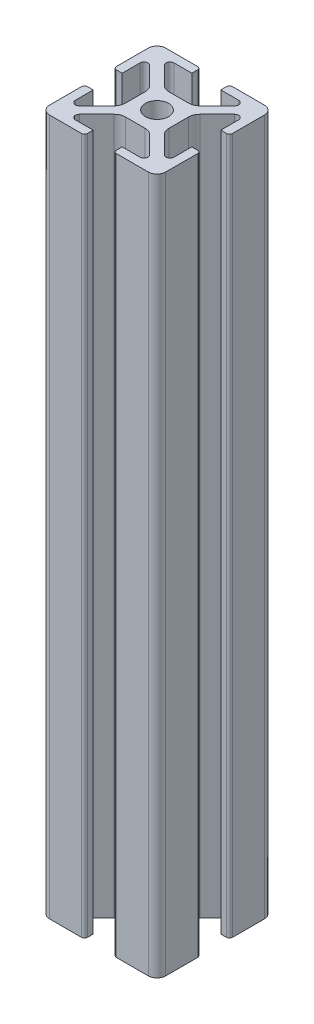
SolidWorks part; units mm, degrees
ref_plane "Plan de face" through (0, 0, 0) normal (0, 0, 1) x (1, 0, 0)
ref_plane "Plan de dessus" through (0, 0, 0) normal (0, 1, 0) x (1, 0, 0)
ref_plane "Plan de droite" through (0, 0, 0) normal (1, 0, 0) x (0, 0, -1)
sketch "Esquisse1" plane through (0, 0, 0) normal (0, 1, 0) x (1, 0, 0)
  line L0 (-5.6497, 11.1927) -> (14.3503, 11.1927) construction
  line L1 (14.3503, 11.1927) -> (14.3503, -8.8073) construction
  line L2 (14.3503, -8.8073) -> (-5.6497, -8.8073) construction
  line L3 (-5.6497, -8.8073) -> (-5.6497, 11.1927) construction
  line L4 (-5.6497, 11.1927) -> (14.3503, -8.8073) construction
  line L5 (-5.6497, -8.8073) -> (14.3503, 11.1927) construction
  line L6 (-5.6497, 9.6927) -> (-5.6497, 4.1927)
  line L7 (-5.1497, 3.6927) -> (-4.1497, 3.6927)
  line L8 (-4.1497, 3.6927) -> (-4.1497, 6.7528)
  line L9 (-2.9547, 7.2478) -> (0.0145, 4.2785)
  line L10 (0.6003, 2.8643) -> (0.6003, -0.4788)
  line L11 (0.0145, -1.8931) -> (-2.9547, -4.8623)
  line L12 (-4.1497, -4.3673) -> (-4.1497, -1.3073)
  line L13 (-4.1497, -1.3073) -> (-5.1497, -1.3073)
  line L14 (-5.6497, -1.8073) -> (-5.6497, -7.3073)
  line L15 (-4.1497, -8.8073) -> (1.3503, -8.8073)
  line L16 (1.8503, -8.3073) -> (1.8503, -7.3073)
  line L17 (1.8503, -7.3073) -> (-1.2098, -7.3073)
  line L18 (-1.7047, -6.1123) -> (1.2645, -3.1431)
  line L19 (2.6787, -2.5573) -> (6.0219, -2.5573)
  line L20 (7.4361, -3.1431) -> (10.4053, -6.1123)
  line L21 (9.9103, -7.3073) -> (6.8503, -7.3073)
  line L22 (6.8503, -7.3073) -> (6.8503, -8.3073)
  line L23 (7.3503, -8.8073) -> (12.8503, -8.8073)
  line L24 (14.3503, -7.3073) -> (14.3503, -1.8073)
  line L25 (13.8503, -1.3073) -> (12.8503, -1.3073)
  line L26 (12.8503, -1.3073) -> (12.8503, -4.3673)
  line L27 (11.6553, -4.8623) -> (8.6861, -1.8931)
  line L28 (8.1003, -0.4788) -> (8.1003, 2.8643)
  line L29 (8.6861, 4.2785) -> (11.6553, 7.2478)
  line L30 (12.8503, 6.7528) -> (12.8503, 3.6927)
  line L31 (12.8503, 3.6927) -> (13.8503, 3.6927)
  line L32 (14.3503, 4.1927) -> (14.3503, 9.6927)
  line L33 (12.8503, 11.1927) -> (7.3503, 11.1927)
  line L34 (6.8503, 10.6927) -> (6.8503, 9.6927)
  line L35 (6.8503, 9.6927) -> (9.9103, 9.6927)
  line L36 (10.4053, 8.4978) -> (7.4361, 5.5285)
  line L37 (6.0219, 4.9427) -> (2.6787, 4.9427)
  line L38 (1.2645, 5.5285) -> (-1.7047, 8.4978)
  line L39 (-1.2098, 9.6927) -> (1.8503, 9.6927)
  line L40 (1.8503, 9.6927) -> (1.8503, 10.6927)
  line L41 (1.3503, 11.1927) -> (-4.1497, 11.1927)
  line L42 (-4.1497, -6.0573) -> (-2.8997, -7.3073) construction
  line L43 (0.6003, -1.3073) -> (1.8503, -2.5573) construction
  line L44 (0.6003, 3.6927) -> (1.8503, 4.9427) construction
  line L45 (-4.1497, 8.4427) -> (-2.8997, 9.6927) construction
  line L46 (12.8503, 8.4427) -> (11.6003, 9.6927) construction
  line L47 (8.1003, 3.6927) -> (6.8503, 4.9427) construction
  line L48 (12.8503, -6.0573) -> (11.6003, -7.3073) construction
  line L49 (8.1003, -1.3073) -> (6.8503, -2.5573) construction
  line L50 (8.1003, 1.1927) -> (0.6003, 1.1927) construction
  line L51 (0.6003, 1.1927) -> (4.3503, 4.9427) construction
  line L52 (4.3503, 4.9427) -> (4.3503, -2.5573) construction
  arc A0 (14.3503, 9.6927) -> (12.8503, 11.1927) centre (12.8503, 9.6927) ccw
  arc A1 (12.8503, -8.8073) -> (14.3503, -7.3073) centre (12.8503, -7.3073) ccw
  arc A2 (-5.6497, -7.3073) -> (-4.1497, -8.8073) centre (-4.1497, -7.3073) ccw
  arc A3 (-5.6497, 9.6927) -> (-4.1497, 11.1927) centre (-4.1497, 9.6927) cw
  arc A4 (-2.9547, -4.8623) -> (-4.1497, -4.3673) centre (-3.4497, -4.3673) cw
  arc A5 (-1.2098, -7.3073) -> (-1.7047, -6.1123) centre (-1.2098, -6.6073) cw
  arc A6 (10.4053, -6.1123) -> (9.9103, -7.3073) centre (9.9103, -6.6073) cw
  arc A7 (12.8503, -4.3673) -> (11.6553, -4.8623) centre (12.1503, -4.3673) cw
  arc A8 (11.6553, 7.2478) -> (12.8503, 6.7528) centre (12.1503, 6.7528) cw
  arc A9 (9.9103, 9.6927) -> (10.4053, 8.4978) centre (9.9103, 8.9927) cw
  arc A10 (-1.7047, 8.4978) -> (-1.2098, 9.6927) centre (-1.2098, 8.9927) cw
  arc A11 (-4.1497, 6.7528) -> (-2.9547, 7.2478) centre (-3.4497, 6.7528) cw
  arc A12 (14.3503, -1.8073) -> (13.8503, -1.3073) centre (13.8503, -1.8073) ccw
  arc A13 (13.8503, 3.6927) -> (14.3503, 4.1927) centre (13.8503, 4.1927) ccw
  arc A14 (7.3503, 11.1927) -> (6.8503, 10.6927) centre (7.3503, 10.6927) ccw
  arc A15 (1.8503, 10.6927) -> (1.3503, 11.1927) centre (1.3503, 10.6927) ccw
  arc A16 (-5.6497, 4.1927) -> (-5.1497, 3.6927) centre (-5.1497, 4.1927) ccw
  arc A17 (-5.1497, -1.3073) -> (-5.6497, -1.8073) centre (-5.1497, -1.8073) ccw
  arc A18 (1.3503, -8.8073) -> (1.8503, -8.3073) centre (1.3503, -8.3073) ccw
  arc A19 (6.8503, -8.3073) -> (7.3503, -8.8073) centre (7.3503, -8.3073) ccw
  arc A20 (6.0219, -2.5573) -> (7.4361, -3.1431) centre (6.0219, -4.5573) cw
  arc A21 (0.0145, 4.2785) -> (0.6003, 2.8643) centre (-1.3997, 2.8643) cw
  arc A22 (0.6003, -0.4788) -> (0.0145, -1.8931) centre (-1.3997, -0.4788) cw
  arc A23 (1.2645, -3.1431) -> (2.6787, -2.5573) centre (2.6787, -4.5573) cw
  arc A24 (8.1003, 2.8643) -> (8.6861, 4.2785) centre (10.1003, 2.8643) cw
  arc A25 (8.6861, -1.8931) -> (8.1003, -0.4788) centre (10.1003, -0.4788) cw
  arc A26 (7.4361, 5.5285) -> (6.0219, 4.9427) centre (6.0219, 6.9427) cw
  arc A27 (2.6787, 4.9427) -> (1.2645, 5.5285) centre (2.6787, 6.9427) cw
  circle A28 centre (4.3503, 1.1927) radius 2
  point P125 (14.3503, -1.3073)
  point P128 (14.3503, 3.6927)
  point P131 (6.8503, 11.1927)
  point P134 (1.8503, 11.1927)
  point P137 (-5.6497, 3.6927)
  point P140 (-5.6497, -1.3073)
  point P143 (1.8503, -8.8073)
  point P146 (6.8503, -8.8073)
  dimension "D33" = 1.5
  dimension "D34" = 0.7
  dimension "D35" = 0.5
  dimension "D36" = 2
  dimension "D1" = 20
  dimension "D2" = 20
  dimension "D3" = 7.5
  dimension "D4" = 7.5
  dimension "7.5" = 7.5
  dimension "D5" = 7.5
  dimension "D6" = 7.5
  dimension "D7" = 7.5
  dimension "D8" = 7.5
  dimension "D9" = 7.5
  dimension "D10" = 7.5
  dimension "D11" = 7.5
  dimension "D12" = 270
  dimension "D13" = 5
  dimension "D14" = 5
  dimension "D15" = 5
  dimension "D16" = 5
  dimension "D17" = 90
  dimension "D18" = 90
  dimension "D19" = 1.5
  dimension "D20" = 135
  dimension "D21" = 1.5
  dimension "D22" = 135
  dimension "D23" = 1.5
  dimension "D24" = 1.5
  dimension "D25" = 1.5
  dimension "D26" = 1.5
  dimension "D27" = 1.5
  dimension "D28" = 90
  dimension "D29" = 90
  dimension "D30" = 90
  dimension "D31" = 90
  dimension "D32" = 90
extrude "Boss.-Extru.1" add sketch "Esquisse1" along normal blind 120
